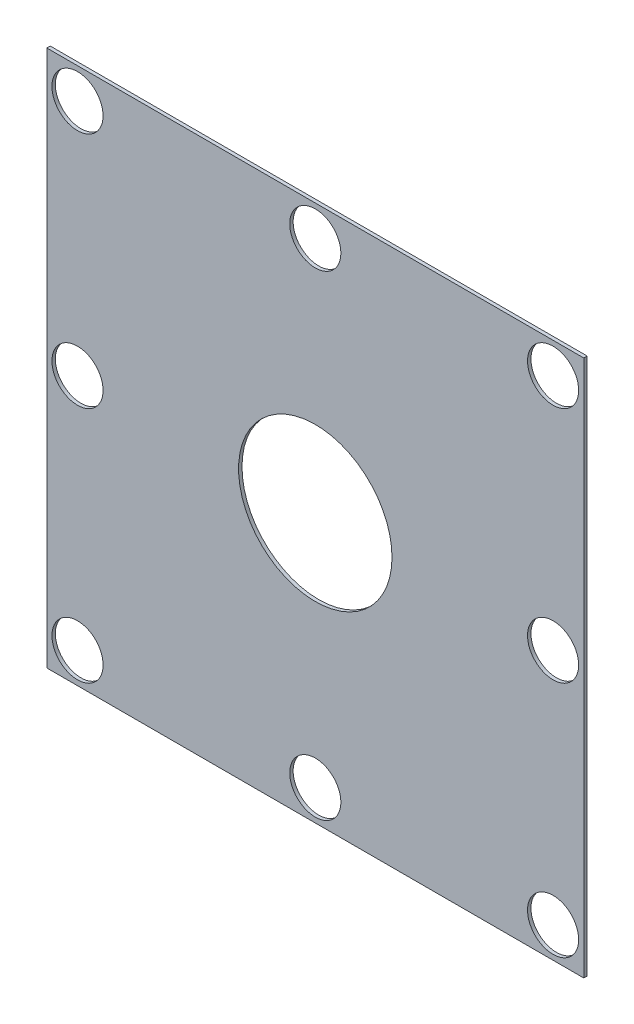
SolidWorks part; units mm, degrees
ref_plane "정면" through (0, 0, 0) normal (0, 0, 1) x (1, 0, 0)
ref_plane "윗면" through (0, 0, 0) normal (0, 1, 0) x (1, 0, 0)
ref_plane "우측면" through (0, 0, 0) normal (1, 0, 0) x (0, 0, -1)
sketch "스케치1" plane through (0, 0, 0) normal (0, 0, 1) x (1, 0, 0)
  line L1 (0, 0) -> (31.5, 0)
  line L2 (0, 0) -> (0, 31.5)
  line L3 (0, 31.5) -> (31.5, 31.5)
  line L4 (31.5, 0) -> (31.5, 31.5)
  dimension "D1" = 31.5
  dimension "D2" = 31.5
extrude "보스-돌출1" add sketch "스케치1" along normal blind 0.2
sketch "스케치2" plane through (0, 0, 0.2) normal (0, 0, 1) x (1, 0, 0)
  line L1 (0, 31.5) -> (0, 0) construction
  line L2 (31.5, 31.5) -> (0, 31.5) construction
  circle A0 centre (15.75, 15.75) radius 4.5
  dimension "D1" = 9
  dimension "D2" = 15.75
  dimension "D3" = 15.75
extrude "컷-돌출1" cut sketch "스케치2" against normal blind 10
sketch "스케치3" plane through (0, 0, 0.2) normal (0, 0, 1) x (1, 0, 0)
  line L1 (31.5, 0) -> (31.5, 31.5) construction
  line L2 (0, 31.5) -> (0, 0) construction
  line L3 (0, 0) -> (31.5, 0) construction
  circle A0 centre (29.7, 15.75) radius 1.5
  circle A1 centre (15.75, 15.75) radius 4.5 construction
  circle A2 centre (15.75, 15.75) radius 4.5
  circle A3 centre (15.75, 1.8) radius 1.5
  circle A4 centre (1.8, 15.75) radius 1.5
  circle A5 centre (15.75, 29.7) radius 1.5
  circle A6 centre (1.8, 29.7) radius 1.5
  circle A7 centre (29.7, 29.7) radius 1.5
  circle A8 centre (29.7, 1.8) radius 1.5
  circle A9 centre (1.8, 1.8) radius 1.5
  point P14 (15.75, 15.75)
  point P29 (15.75, 15.75)
  dimension "D1" = 3
  dimension "D6" = 3
  dimension "D3" = 1.8
  dimension "D4" = 1.8
  dimension "D5" = 1.8
  dimension "D8" = 1.8
  dimension "D9" = 1.8
  dimension "D2" = 4
  dimension "D7" = 4
extrude "컷-돌출2" cut sketch "스케치3" against normal blind 0.2
